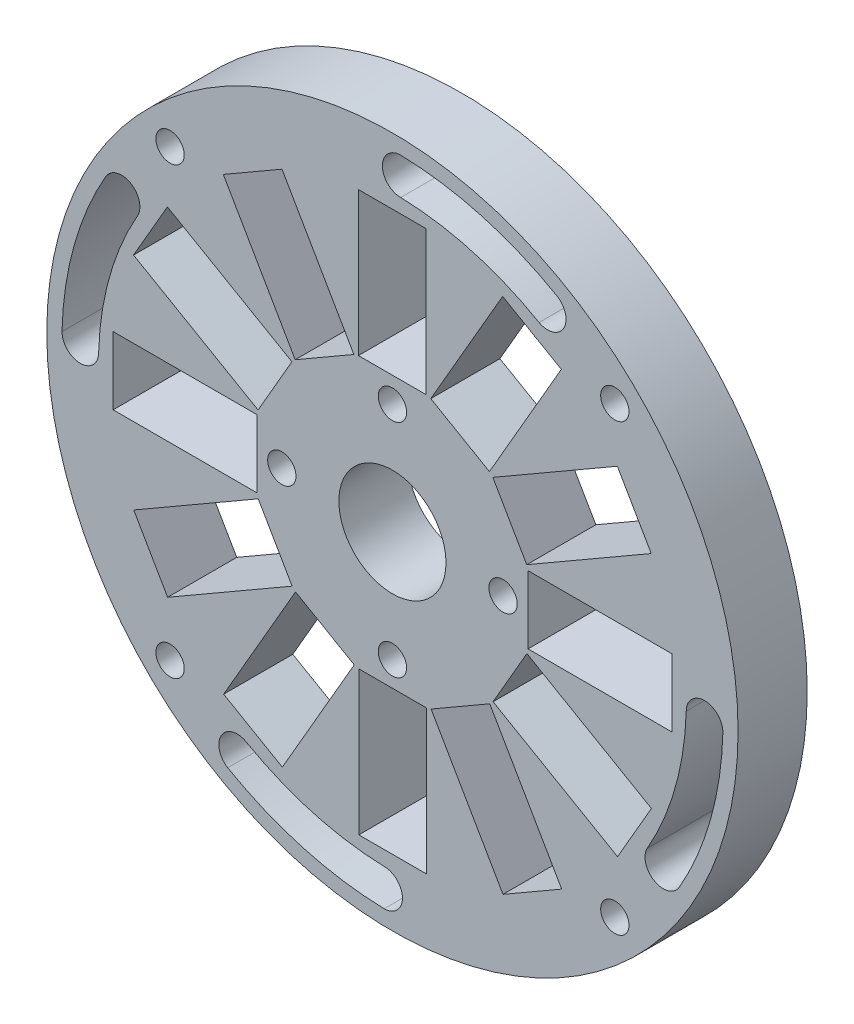
SolidWorks part; units mm, degrees
material "AISI 304"
ref_plane "Alzado" through (0, 0, 0) normal (1, 0, 0) x (0, 1, 0)
ref_plane "Planta" through (0, 0, 0) normal (0, 0, 1) x (0, 1, 0)
ref_plane "Vista lateral" through (0, 0, 0) normal (0, 1, 0) x (-1, 0, 0)
sketch "Croquis1" plane through (0, 0, 0) normal (0, 0, 1) x (0, 1, 0)
  line L0 (15.9642, 37.4508) -> (5.5642, 19.4375)
  line L1 (-4.9, 40.4) -> (4.9, 40.4)
  line L2 (-4.9, 40.4) -> (-4.9, 19.6)
  line L3 (-4.9, 19.6) -> (4.9, 19.6)
  line L4 (4.9, 40.4) -> (4.9, 19.6)
  line L5 (-4.9, 40.4) -> (4.9, 19.6) construction
  line L6 (-4.9, 19.6) -> (4.9, 40.4) construction
  line L7 (15.9642, 37.4508) -> (24.4513, 32.5508)
  line L8 (24.4513, 32.5508) -> (14.0513, 14.5375)
  line L9 (5.5642, 19.4375) -> (14.0513, 14.5375)
  line L10 (32.5586, 24.4647) -> (14.5452, 14.0647)
  line L11 (32.5586, 24.4647) -> (37.4586, 15.9776)
  line L12 (37.4586, 15.9776) -> (19.4452, 5.5776)
  line L13 (14.5452, 14.0647) -> (19.4452, 5.5776)
  line L14 (40.4366, 4.9211) -> (19.6366, 4.9211)
  line L15 (40.4366, 4.9211) -> (40.4366, -4.8789)
  line L16 (40.4366, -4.8789) -> (19.6366, -4.8789)
  line L17 (19.6366, 4.9211) -> (19.6366, -4.8789)
  line L18 (37.4874, -15.9431) -> (19.4741, -5.5431)
  line L19 (37.4874, -15.9431) -> (32.5874, -24.4301)
  line L20 (32.5874, -24.4301) -> (14.5741, -14.0301)
  line L21 (19.4741, -5.5431) -> (14.5741, -14.0301)
  line L22 (24.5013, -32.5374) -> (14.1013, -14.5241)
  line L23 (24.5013, -32.5374) -> (16.0142, -37.4374)
  line L24 (16.0142, -37.4374) -> (5.6142, -19.4241)
  line L25 (14.1013, -14.5241) -> (5.6142, -19.4241)
  line L26 (4.9577, -40.4155) -> (4.9577, -19.6155)
  line L27 (4.9577, -40.4155) -> (-4.8423, -40.4155)
  line L28 (-4.8423, -40.4155) -> (-4.8423, -19.6155)
  line L29 (4.9577, -19.6155) -> (-4.8423, -19.6155)
  line L30 (-15.9065, -37.4663) -> (-5.5065, -19.453)
  line L31 (-15.9065, -37.4663) -> (-24.3935, -32.5663)
  line L32 (-24.3935, -32.5663) -> (-13.9935, -14.553)
  line L33 (-5.5065, -19.453) -> (-13.9935, -14.553)
  line L34 (-32.5008, -24.4801) -> (-14.4875, -14.0801)
  line L35 (-32.5008, -24.4801) -> (-37.4008, -15.9931)
  line L36 (-37.4008, -15.9931) -> (-19.3875, -5.5931)
  line L37 (-14.4875, -14.0801) -> (-19.3875, -5.5931)
  line L38 (-40.3789, -4.9366) -> (-19.5789, -4.9366)
  line L39 (-40.3789, -4.9366) -> (-40.3789, 4.8634)
  line L40 (-40.3789, 4.8634) -> (-19.5789, 4.8634)
  line L41 (-19.5789, -4.9366) -> (-19.5789, 4.8634)
  line L42 (-37.4297, 15.9276) -> (-19.4164, 5.5276)
  line L43 (-37.4297, 15.9276) -> (-32.5297, 24.4147)
  line L44 (-32.5297, 24.4147) -> (-14.5164, 14.0147)
  line L45 (-19.4164, 5.5276) -> (-14.5164, 14.0147)
  line L46 (-24.4435, 32.522) -> (-14.0435, 14.5086)
  line L47 (-24.4435, 32.522) -> (-15.9565, 37.422)
  line L48 (-15.9565, 37.422) -> (-5.5565, 19.4086)
  line L49 (-14.0435, 14.5086) -> (-5.5565, 19.4086)
  arc A9 (47.8, -1.2005) -> (42.5, -1.2005) centre (45.15, -1.2005) ccw
  arc A10 (1.2005, 47.8) -> (1.2005, 42.5) centre (1.2005, 45.15) ccw
  arc A11 (21.2105, 36.8484) -> (23.8278, 41.455) centre (22.459, 39.1859) ccw
  arc A12 (1.2005, 47.8) -> (23.8278, 41.455) centre (0, 0) cw
  arc A13 (1.2005, 42.5) -> (21.2105, 36.8484) centre (0, 0) cw
  arc A26 (42.5, -1.2005) -> (36.8484, -21.2105) centre (0, 0) cw
  arc A27 (36.8484, -21.2105) -> (41.455, -23.8278) centre (39.1859, -22.459) ccw
  arc A28 (47.8, -1.2005) -> (41.455, -23.8278) centre (0, 0) cw
  arc A29 (-1.2005, -47.8) -> (-1.2005, -42.5) centre (-1.2005, -45.15) ccw
  arc A30 (-1.2005, -42.5) -> (-21.2105, -36.8484) centre (0, 0) cw
  arc A31 (-21.2105, -36.8484) -> (-23.8278, -41.455) centre (-22.459, -39.1859) ccw
  arc A32 (-1.2005, -47.8) -> (-23.8278, -41.455) centre (0, 0) cw
  arc A33 (-47.8, 1.2005) -> (-42.5, 1.2005) centre (-45.15, 1.2005) ccw
  arc A34 (-42.5, 1.2005) -> (-36.8484, 21.2105) centre (0, 0) cw
  arc A35 (-36.8484, 21.2105) -> (-41.455, 23.8278) centre (-39.1859, 22.459) ccw
  arc A36 (-47.8, 1.2005) -> (-41.455, 23.8278) centre (0, 0) cw
  point P3 (0, 30)
  point P57 (0.0289, -0.0077)
  point P58 (-0.0005, 0.0001)
  point P64 (0, 0)
  point P78 (0, 0)
  point P82 (0, 0)
  point P84 (0, 0)
  dimension "D5" = 4.75
  dimension "D10" = 2.65
  dimension "D6" = 5.3
  dimension "D12" = 2.65
  dimension "D1" = 20.8
  dimension "D2" = 9.8
  dimension "D3" = 0
  dimension "D4" = 30
  dimension "D7" = 2
  dimension "D9" = 4
  dimension "D11" = 4.75
  dimension "D8" = 12
sketch "Croquis2" plane through (0, 0, 0) normal (0, 0, 1) x (0, 1, 0)
  circle A0 centre (0, 0) radius 50
extrude "Saliente-Extruir1" add sketch "Croquis2" along normal blind 10
extrude "Cortar-Extruir3" cut sketch "Croquis1" along normal through all
sketch "Croquis4" plane through (0, 0, 10) normal (0, 0, 1) x (1, 0, 0)
  circle A0 centre (0, 0) radius 7.75
  dimension "D1" = 15.5
extrude "Cortar-Extruir4" cut sketch "Croquis4" against normal blind 10
sketch "Croquis5" plane through (0, 0, 10) normal (0, 0, 1) x (1, 0, 0)
  circle A1 centre (0, 16) radius 2.05
  circle A2 centre (16, 0) radius 2.05
  circle A3 centre (0, -16) radius 2.05
  circle A4 centre (-16, 0) radius 2.05
  point P14 (0, 0)
  dimension "D1" = 16
  dimension "D2" = 4.1
  dimension "D3" = 4
extrude "Cortar-Extruir5" cut sketch "Croquis5" against normal blind 10
cosmetic thread "Rosca cosmética1" parameters "D2"=5
cosmetic thread "Rosca cosmética2" parameters "D2"=5
cosmetic thread "Rosca cosmética3" parameters "D2"=5
cosmetic thread "Rosca cosmética4" parameters "D2"=5
sketch "Croquis6" plane through (0, 0, 10) normal (0, 0, 1) x (1, 0, 0)
  circle A0 centre (-32.17, 32.17) radius 2.05
  circle A2 centre (32.17, 32.17) radius 2.05
  circle A3 centre (32.17, -32.17) radius 2.05
  circle A4 centre (-32.17, -32.17) radius 2.05
  point P12 (0, 0)
  dimension "D1" = 4.1
  dimension "D2" = 32.17
  dimension "D3" = 32.17
  dimension "D4" = 4
extrude "Cortar-Extruir6" cut sketch "Croquis6" against normal blind 6
cosmetic thread "Rosca cosmética5" parameters "D2"=5
cosmetic thread "Rosca cosmética6" parameters "D2"=5
cosmetic thread "Rosca cosmética7" parameters "D2"=5
cosmetic thread "Rosca cosmética8" parameters "D2"=4.2
